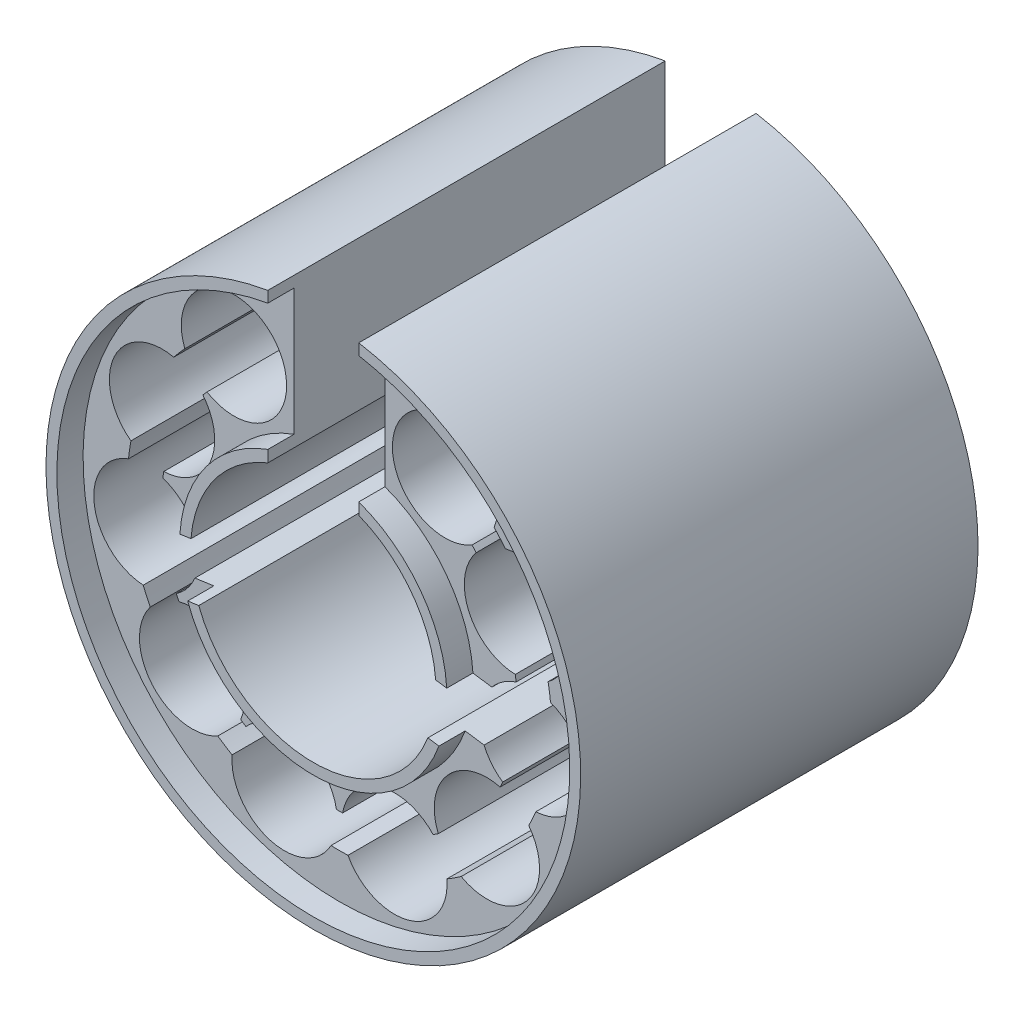
SolidWorks part; units mm, degrees
other "Markup1"
sketch "Sketch1"
material "PBT General Purpose"
ref_plane "Front Plane" through (0, 0, 0) normal (0, 0, 1) x (1, 0, 0)
ref_plane "Top Plane" through (0, 0, 0) normal (0, 1, 0) x (1, 0, 0)
ref_plane "Right Plane" through (0, 0, 0) normal (1, 0, 0) x (0, 0, -1)
sketch "Basic_Shape_Sketch" plane through (0, 0, 0) normal (0, 0, 1) x (1, 0, 0)
  circle A0 centre (0, 0) radius 22.5
  circle A1 centre (0, 0) radius 49
  dimension "D1" = 45
  dimension "D2" = 98
extrude "Basic_Shape" add sketch "Basic_Shape_Sketch" along normal blind 68.03
sketch "Slit_Sketch" plane through (0, 0, 68.03) normal (0, 0, 1) x (1, 0, 0)
  line L0 (-8.33, 48.2868) -> (-8.33, 20.9012)
  line L1 (8.33, 48.2868) -> (8.33, 20.9012)
  line L3 (-8.33, 20.9012) -> (8.33, 20.9012)
  circle A0 centre (0, 0) radius 49 construction
  circle A1 centre (0, 0) radius 22.5 construction
  arc A2 (-8.33, 48.2868) -> (8.33, 48.2868) centre (0, 48.2868) cw
  dimension "D1" = 16.66
extrude "Slit" cut sketch "Slit_Sketch" against normal through all
sketch "Battery_Slot_Sketch" plane through (0, 0, 68.03) normal (0, 0, 1) x (1, 0, 0)
  line L0 (0, 0) -> (0, -49) construction
  line L1 (0, 0) -> (-6.3376, -21.589) construction
  line L3 (-6.3376, -21.589) -> (-10.0698, -34.3025) construction
  line L4 (-10.0698, -34.3025) -> (-13.8019, -47.016) construction
  circle A0 centre (-10.0698, -34.3025) radius 9.65
  arc A1 (-8.33, 48.2868) -> (8.33, 48.2868) centre (0, 0) ccw construction
  arc A8 (-8.33, 20.9012) -> (8.33, 20.9012) centre (0, 0) ccw construction
  dimension "D1" = 19.3
  dimension "D2" = 16.36
extrude "Battery_Slot" cut sketch "Battery_Slot_Sketch" against normal blind 67.03
pattern_circular "Pattern_Battery_Slot" count 5 every 32.72 about axis through (0, 0, 0) along (0, 0, 1) of "Battery_Slot"
mirror "Mirror_Battery_Slot" about plane through (0, 0, 0) normal (1, 0, 0) of "Battery_Slot", "Pattern_Battery_Slot"
sketch "Bus_Slit_Sketch" plane through (0, 0, 68.03) normal (0, 0, 1) x (1, 0, 0)
  arc A2 (-9.7545, 31.1326) -> (9.7545, 31.1326) centre (0, 0) ccw
  circle A3 centre (-19.3451, 30.0638) radius 9.65 construction
  circle A4 centre (19.3451, 30.0638) radius 9.65 construction
  arc A5 (-12.4591, 36.8244) -> (12.4591, 36.8244) centre (0, 0) ccw
  circle A6 centre (-19.3451, 30.0638) radius 9.65 construction
  arc A7 (-12.4591, 36.8244) -> (-9.7545, 31.1326) centre (-19.3451, 30.0638) cw
  arc A8 (9.7545, 31.1326) -> (12.4591, 36.8244) centre (19.3451, 30.0638) cw
  dimension "D1" = 38.875
  dimension "D2" = 32.625
  dimension "D3" = 9.65
  dimension "D4" = 9.65
extrude "Bus_Slit" cut sketch "Bus_Slit_Sketch" against normal blind 67.03
sketch "Cap_Inner_Lip_Sketch" plane through (0, 0, 68.03) normal (0, 0, 1) x (1, 0, 0)
  line L0 (8.33, 20.9012) -> (8.33, 48.2868) construction
  line L1 (-8.33, 48.2868) -> (-8.33, 20.9012) construction
  line L2 (-8.33, 23.0404) -> (-8.33, 20.9012)
  line L3 (8.33, 23.0404) -> (8.33, 20.9012)
  arc A0 (-8.33, 20.9012) -> (8.33, 20.9012) centre (0, 0) ccw
  arc A1 (-8.33, 23.0404) -> (8.33, 23.0404) centre (0, 0) ccw
  dimension "D1" = 24.5
extrude "Cap_Inner_Lip" add sketch "Cap_Inner_Lip_Sketch" along normal blind 4.8
sketch "Cap_Outer_Lip_Sketch" plane through (0, 0, 68.03) normal (0, 0, 1) x (1, 0, 0)
  line L0 (-8.33, 48.2868) -> (-8.33, 23.0404) construction
  line L1 (8.33, 23.0404) -> (8.33, 48.2868) construction
  line L2 (-8.33, 48.2868) -> (-8.33, 46.2559)
  line L3 (8.33, 48.2868) -> (8.33, 46.2559)
  arc A0 (-8.33, 48.2868) -> (8.33, 48.2868) centre (0, 0) ccw
  arc A1 (-8.33, 48.2868) -> (8.33, 48.2868) centre (0, 0) ccw construction
  arc A2 (-8.33, 46.2559) -> (8.33, 46.2559) centre (0, 0) ccw
  dimension "D1" = 47
extrude "Cap_Outer_Lip" add sketch "Cap_Outer_Lip_Sketch" along normal blind 4.8
sketch "Wire_Slits_Sketch" plane through (0, 0, 68.03) normal (0, 0, 1) x (1, 0, 0)
  line L0 (-44.9358, -6.4754) -> (0, 0) construction
  line L3 (-33.5, -4.8274) -> (-16.5, -2.3777) construction
  line L4 (-34.2131, 0.1215) -> (-17.2131, 2.5712)
  line L5 (-32.7869, -9.7763) -> (-15.7869, -7.3266)
  line L6 (0, -40.0576) -> (0, 40.0576) construction
  line L7 (33.5, -4.8274) -> (16.5, -2.3777) construction
  line L8 (34.2131, 0.1215) -> (17.2131, 2.5712)
  line L9 (32.7869, -9.7763) -> (15.7869, -7.3266)
  arc A2 (-38.6713, 3.974) -> (-35.9759, -14.7308) centre (-35.3845, -5.099) ccw construction
  arc A3 (-34.2131, 0.1215) -> (-32.7869, -9.7763) centre (-33.5, -4.8274) ccw
  arc A4 (-15.7869, -7.3266) -> (-17.2131, 2.5712) centre (-16.5, -2.3777) ccw
  arc A5 (34.2131, 0.1215) -> (32.7869, -9.7763) centre (33.5, -4.8274) cw
  arc A6 (15.7869, -7.3266) -> (17.2131, 2.5712) centre (16.5, -2.3777) cw
  point P7 (-25, -3.6026)
  point P18 (25, -3.6026)
  dimension "D3" = 17
  dimension "D1" = 10
  dimension "D2" = 25
extrude "Wire_Slits" cut sketch "Wire_Slits_Sketch" against normal blind 67.03 and the other way through all
sketch "Penny Hole Sketch" plane through (0, 0, 1) normal (0, 0, 1) x (1, 0, 0)
  line L0 (-17.6027, 27.3559) -> (0, 0) construction
  line L1 (-19.3451, 30.0638) -> (-17.6027, 27.3559) construction
  circle A0 centre (-17.6027, 27.3559) radius 9.65
  arc A1 (-24.292, 21.7782) -> (-28.3513, 26.5983) centre (-19.3451, 30.0638) ccw construction
  dimension "D1" = 32.53
extrude "Penny Hole" cut sketch "Penny Hole Sketch" against normal through all
mirror "Penny Hole Mirror" about plane through (0, 0, 0) normal (1, 0, 0) of "Penny Hole"
